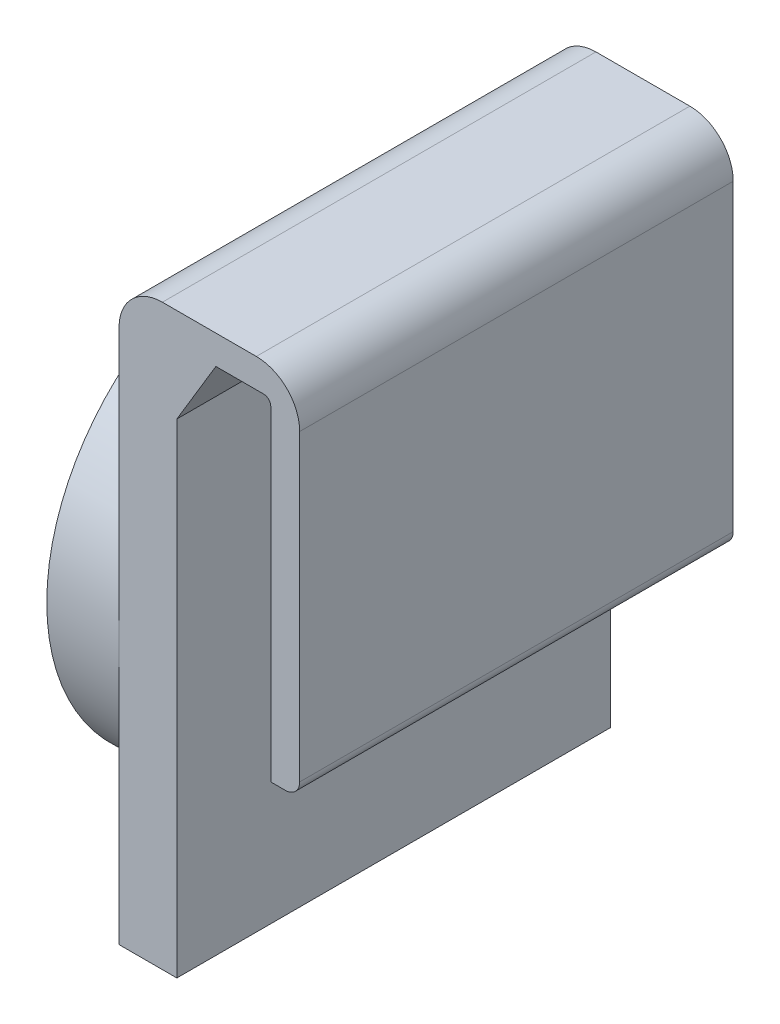
SolidWorks part; units mm, degrees
ref_plane "Front Plane" through (0, 0, 0) normal (0, 0, 1) x (1, 0, 0)
ref_plane "Top Plane" through (0, 0, 0) normal (0, 1, 0) x (1, 0, 0)
ref_plane "Right Plane" through (0, 0, 0) normal (1, 0, 0) x (0, 0, -1)
sketch "Sketch1" plane through (0, 0, 0) normal (0, 0, 1) x (1, 0, 0)
  line L0 (0, 0) -> (0, 40)
  line L1 (0, 40) -> (12.5, 40)
  line L2 (12.5, 40) -> (12.5, 15)
  line L3 (12.5, 15) -> (10.5, 15)
  line L4 (10.5, 15) -> (10.5, 38)
  line L5 (10.5, 38) -> (6.7, 38)
  line L6 (6.7, 38) -> (4, 33.5)
  line L7 (4, 33.5) -> (4, 0)
  line L8 (4, 0) -> (0, 0)
  dimension "D1" = 3.8
  dimension "D2" = 2.7
  dimension "D3" = 2
  dimension "D4" = 2
  dimension "D5" = 4
  dimension "D6" = 4.5
  dimension "D7" = 25
  dimension "D8" = 40
extrude "Boss-Extrude1" add sketch "Sketch1" along normal blind 30
fillet "Fillet1" radius 3 2 edges at (12.5, 40, 15) (0, 40, 15)
fillet "Fillet2" radius 0.5 1 edges at (10.5, 38, 15)
fillet "Fillet3" radius 1 1 edges at (12.5, 15, 15)
sketch "Sketch3" plane through (0, 0, 0) normal (-1, 0, 0) x (0, 0, 1)
  line L0 (30, 37) -> (0, 37) construction
  circle A0 centre (15, 18) radius 15
  dimension "D1" = 30
  dimension "D2" = 19
extrude "Boss-Extrude2" add sketch "Sketch3" along normal blind 5
sketch "Sketch4" plane through (-5, 0, 0) normal (-1, 0, 0) x (0, 0, 1)
  circle A0 centre (15, 18) radius 10.5
  dimension "D1" = 21
extrude "Cut-Extrude2" cut sketch "Sketch4" against normal blind 7
